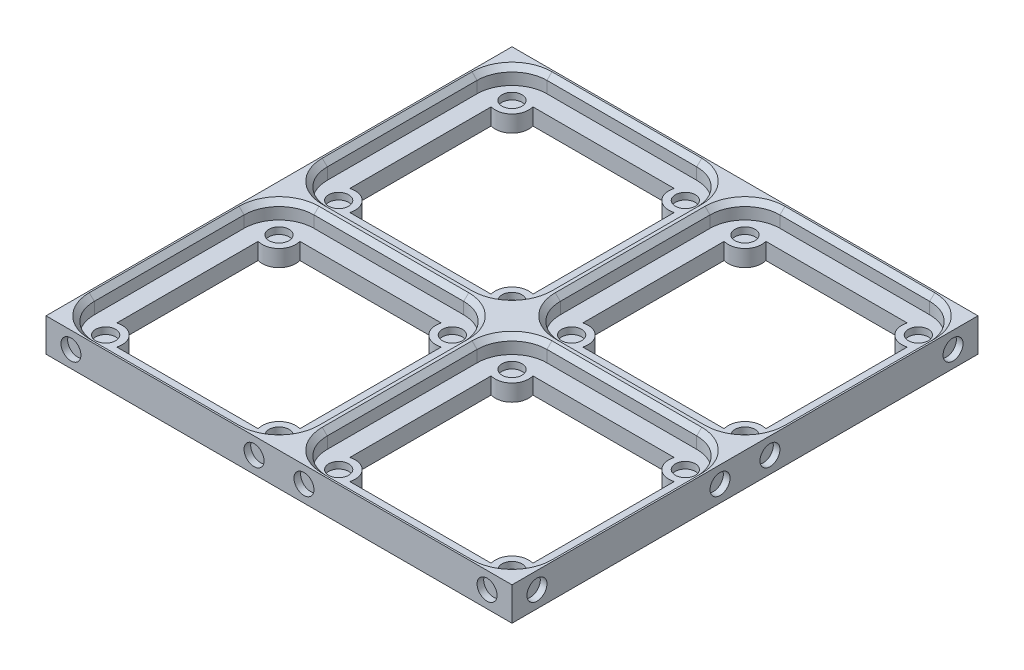
SolidWorks part; units mm, degrees
ref_plane "Front Plane" through (0, 0, 0) normal (0, 0, 1) x (1, 0, 0)
ref_plane "Top Plane" through (0, 0, 0) normal (0, 1, 0) x (1, 0, 0)
ref_plane "Right Plane" through (0, 0, 0) normal (1, 0, 0) x (0, 0, -1)
sketch "Sketch1" plane through (0, 0, 0) normal (0, 1, 0) x (1, 0, 0)
  line L1 (0, 0) -> (70, 0)
  line L2 (0, 0) -> (0, 70)
  line L3 (0, 70) -> (70, 70)
  line L4 (70, 0) -> (70, 70)
  dimension "D1" = 70
  dimension "D2" = 70
extrude "Boss-Extrude2" add sketch "Sketch1" along normal blind 7
sketch "Sketch3" plane through (0, 7, 0) normal (0, 1, 0) x (1, 0, 0)
  line L8 (2.5, 67.5) -> (2.5, 2.5)
  line L9 (2.5, 2.5) -> (67.5, 2.5)
  line L10 (67.5, 2.5) -> (67.5, 67.5)
  line L11 (67.5, 67.5) -> (2.5, 67.5)
  line L12 (2.5, 57.5) -> (2.5, 12.5)
  line L13 (12.5, 2.5) -> (57.5, 2.5)
  line L14 (67.5, 12.5) -> (67.5, 57.5)
  line L15 (57.5, 67.5) -> (12.5, 67.5)
  arc A0 (2.5, 12.5) -> (12.5, 2.5) centre (12.5, 12.5) ccw
  arc A1 (57.5, 2.5) -> (67.5, 12.5) centre (57.5, 12.5) ccw
  arc A2 (67.5, 57.5) -> (57.5, 67.5) centre (57.5, 57.5) ccw
  arc A3 (2.5, 57.5) -> (12.5, 67.5) centre (12.5, 57.5) cw
  dimension "D2" = 10
  dimension "D1" = 2.5
extrude "Cut-Extrude1" cut sketch "Sketch3" against normal blind 5
sketch "Sketch9" plane through (0, 0, 0) normal (0, -1, 0) x (1, 0, 0)
  line L1 (0, -70) -> (70, -70)
  line L2 (0, -70) -> (0, 0)
  line L3 (0, 0) -> (70, 0)
  line L4 (70, -70) -> (70, 0)
extrude "Boss-Extrude3" add sketch "Sketch9" along normal blind 5
sketch "Sketch20" plane through (0, 2, 0) normal (0, 1, 0) x (1, 0, 0)
  line L0 (35, 35) -> (8.9645, 61.0355) construction
  line L19 (12.5, 7.5) -> (57.5, 7.5)
  line L20 (62.5, 12.5) -> (62.5, 57.5)
  line L21 (57.5, 62.5) -> (12.5, 62.5)
  line L22 (7.5, 57.5) -> (7.5, 12.5)
  line L23 (13.7452, 7.5) -> (56.2548, 7.5)
  line L24 (62.5, 13.7452) -> (62.5, 56.2548)
  line L25 (56.2548, 62.5) -> (13.7452, 62.5)
  line L26 (7.5, 56.2548) -> (7.5, 13.7452)
  arc A0 (56.2548, 62.5) -> (62.5, 56.2548) centre (61.0355, 61.0355) ccw
  arc A1 (62.5, 13.7452) -> (56.2548, 7.5) centre (61.0355, 8.9645) ccw
  arc A2 (13.7452, 7.5) -> (7.5, 13.7452) centre (8.9645, 8.9645) ccw
  circle A4 centre (8.9645, 61.0355) radius 3
  circle A5 centre (8.9645, 8.9645) radius 3
  circle A6 centre (61.0355, 8.9645) radius 3
  circle A7 centre (61.0355, 61.0355) radius 3
  arc A21 (7.5, 56.2548) -> (13.7452, 62.5) centre (8.9645, 61.0355) ccw
  arc A24 (7.5, 12.5) -> (12.5, 7.5) centre (12.5, 12.5) ccw
  arc A25 (57.5, 7.5) -> (62.5, 12.5) centre (57.5, 12.5) ccw
  arc A26 (62.5, 57.5) -> (57.5, 62.5) centre (57.5, 57.5) ccw
  arc A27 (12.5, 62.5) -> (7.5, 57.5) centre (12.5, 57.5) ccw
  point P8 (35, 35)
  dimension "D2" = 6
  dimension "D3" = 4
  dimension "D4" = 36.8198
  dimension "D1" = 5
extrude "Cut-Extrude11" cut sketch "Sketch20" against normal through all contours L23 A1 L24 A0 L25 A21 L26 A2
sketch "Sketch21" plane through (0, 2, 0) normal (0, 1, 0) x (1, 0, 0)
  circle A0 centre (8.9645, 61.0355) radius 3
  circle A1 centre (61.0355, 61.0355) radius 3
  circle A2 centre (61.0355, 8.9645) radius 3
  circle A3 centre (8.9645, 8.9645) radius 3
extrude "Cut-Extrude12" cut sketch "Sketch21" against normal blind 2 contours A0 | A1 | A2 | A3
sketch "Sketch22" plane through (0, -5, 0) normal (0, -1, 0) x (1, 0, 0)
  line L0 (7.5, -13.7452) -> (7.5, -56.2548)
  line L1 (0, 0) -> (70, 0)
  line L2 (0, 0) -> (0, -70)
  line L3 (0, -70) -> (70, -70)
  line L4 (70, 0) -> (70, -70)
  line L6 (13.7452, -62.5) -> (56.2548, -62.5)
  line L8 (62.5, -56.2548) -> (62.5, -13.7452)
  line L10 (56.2548, -7.5) -> (13.7452, -7.5)
  arc A0 (7.5, -13.7452) -> (13.7452, -7.5) centre (8.9645, -8.9645) ccw
  arc A1 (56.2548, -7.5) -> (62.5, -13.7452) centre (61.0355, -8.9645) ccw
  arc A2 (62.5, -56.2548) -> (56.2548, -62.5) centre (61.0355, -61.0355) ccw
  arc A3 (13.7452, -62.5) -> (7.5, -56.2548) centre (8.9645, -61.0355) ccw
extrude "Cut-Extrude13" cut sketch "Sketch22" against normal blind 2
ref_plane "Plane2" through (0, 0, -35) normal (0, 0, 1) x (1, 0, 0)
ref_plane "Plane3" through (35, 0, 0) normal (-1, 0, 0) x (0, 0, 1)
sketch "Sketch27" plane through (0, 0, 0) normal (-1, 0, 0) x (0, 0, 1)
  line L0 (-70, -3) -> (-70, 7)
  line L1 (-70, 7) -> (-70, 2)
  line L2 (-70, 2) -> (-62.5, 2)
  line L3 (-35, -5.5) -> (-35, 5.5) construction
  circle A0 centre (-62.5, 2) radius 3
  circle A1 centre (-7.5, 2) radius 3
extrude "Cut-Extrude27" cut sketch "Sketch27" against normal blind 2
sketch "Sketch28" plane through (0, 0, 0) normal (0, 0, 1) x (1, 0, 0)
  line L0 (0, -3) -> (0, 7)
  line L1 (0, 7) -> (0, 2)
  line L2 (0, 2) -> (7.5, 2)
  line L3 (35, 5.5) -> (35, -5.5) construction
  circle A0 centre (7.5, 2) radius 3
  circle A1 centre (62.5, 2) radius 3
extrude "Cut-Extrude28" cut sketch "Sketch28" against normal blind 2
mirror "Mirror2" about plane through (0, 7, -70) normal (0, 0, 1) of bodies 126
mirror "Mirror3" about plane through (70, 7, 0) normal (-1, 0, 0) of bodies 130
sketch "Sketch30" plane through (0, 7, 0) normal (0, 1, 0) x (1, 0, 0)
  line L20 (2, 57.5) -> (2, 12.5)
  line L21 (12.5, 2) -> (57.5, 2)
  line L22 (68, 12.5) -> (68, 57.5)
  line L23 (57.5, 68) -> (12.5, 68)
  line L24 (2, 57.5) -> (2, 12.5)
  line L25 (12.5, 2) -> (57.5, 2)
  line L26 (68, 12.5) -> (68, 57.5)
  line L27 (57.5, 68) -> (12.5, 68)
  arc A24 (2, 12.5) -> (12.5, 2) centre (12.5, 12.5) ccw
  arc A25 (57.5, 2) -> (68, 12.5) centre (57.5, 12.5) ccw
  arc A26 (68, 57.5) -> (57.5, 68) centre (57.5, 57.5) ccw
  arc A27 (12.5, 68) -> (2, 57.5) centre (12.5, 57.5) ccw
  arc A28 (2, 12.5) -> (12.5, 2) centre (12.5, 12.5) ccw
  arc A29 (57.5, 2) -> (68, 12.5) centre (57.5, 12.5) ccw
  arc A30 (68, 57.5) -> (57.5, 68) centre (57.5, 57.5) ccw
  arc A31 (12.5, 68) -> (2, 57.5) centre (12.5, 57.5) ccw
  dimension "D1" = 0.5
extrude "Cut-Extrude29" cut sketch "Sketch30" against normal blind 5
sketch "Sketch31" plane through (0, 7, 0) normal (0, 1, 0) x (1, 0, 0)
  line L546 (68, 82.5) -> (68, 127.5)
  line L547 (12.5, 72) -> (57.5, 72)
  line L548 (2, 127.5) -> (2, 82.5)
  line L549 (57.5, 138) -> (12.5, 138)
  line L550 (68, 82.5) -> (68, 127.5)
  line L551 (12.5, 72) -> (57.5, 72)
  line L552 (2, 127.5) -> (2, 82.5)
  line L553 (57.5, 138) -> (12.5, 138)
  line L574 (82.5, 72) -> (127.5, 72)
  line L575 (138, 82.5) -> (138, 127.5)
  line L576 (72, 127.5) -> (72, 82.5)
  line L577 (127.5, 138) -> (82.5, 138)
  line L578 (82.5, 72) -> (127.5, 72)
  line L579 (138, 82.5) -> (138, 127.5)
  line L580 (72, 127.5) -> (72, 82.5)
  line L581 (127.5, 138) -> (82.5, 138)
  line L599 (72, 57.5) -> (72, 12.5)
  line L600 (82.5, 2) -> (127.5, 2)
  line L601 (138, 12.5) -> (138, 57.5)
  line L602 (127.5, 68) -> (82.5, 68)
  line L603 (72, 57.5) -> (72, 12.5)
  line L604 (82.5, 2) -> (127.5, 2)
  line L605 (138, 12.5) -> (138, 57.5)
  line L606 (127.5, 68) -> (82.5, 68)
  arc A564 (68, 127.5) -> (57.5, 138) centre (57.5, 127.5) ccw
  arc A565 (57.5, 72) -> (68, 82.5) centre (57.5, 82.5) ccw
  arc A566 (2, 82.5) -> (12.5, 72) centre (12.5, 82.5) ccw
  arc A567 (12.5, 138) -> (2, 127.5) centre (12.5, 127.5) ccw
  arc A568 (68, 127.5) -> (57.5, 138) centre (57.5, 127.5) ccw
  arc A569 (57.5, 72) -> (68, 82.5) centre (57.5, 82.5) ccw
  arc A570 (2, 82.5) -> (12.5, 72) centre (12.5, 82.5) ccw
  arc A571 (12.5, 138) -> (2, 127.5) centre (12.5, 127.5) ccw
  arc A588 (72, 82.5) -> (82.5, 72) centre (82.5, 82.5) ccw
  arc A589 (127.5, 72) -> (138, 82.5) centre (127.5, 82.5) ccw
  arc A590 (138, 127.5) -> (127.5, 138) centre (127.5, 127.5) ccw
  arc A591 (82.5, 138) -> (72, 127.5) centre (82.5, 127.5) ccw
  arc A592 (72, 82.5) -> (82.5, 72) centre (82.5, 82.5) ccw
  arc A593 (127.5, 72) -> (138, 82.5) centre (127.5, 82.5) ccw
  arc A594 (138, 127.5) -> (127.5, 138) centre (127.5, 127.5) ccw
  arc A595 (82.5, 138) -> (72, 127.5) centre (82.5, 127.5) ccw
  arc A615 (72, 12.5) -> (82.5, 2) centre (82.5, 12.5) ccw
  arc A616 (127.5, 2) -> (138, 12.5) centre (127.5, 12.5) ccw
  arc A617 (138, 57.5) -> (127.5, 68) centre (127.5, 57.5) ccw
  arc A618 (82.5, 68) -> (72, 57.5) centre (82.5, 57.5) ccw
  arc A619 (72, 12.5) -> (82.5, 2) centre (82.5, 12.5) ccw
  arc A620 (127.5, 2) -> (138, 12.5) centre (127.5, 12.5) ccw
  arc A621 (138, 57.5) -> (127.5, 68) centre (127.5, 57.5) ccw
  arc A622 (82.5, 68) -> (72, 57.5) centre (82.5, 57.5) ccw
  dimension "D1" = 0.5
  dimension "D2" = 0.5
  dimension "D3" = 0.5
extrude "Cut-Extrude30" cut sketch "Sketch31" against normal blind 5
chamfer "Chamfer1" distance 1.5 angle 45 32 edges at (134.9246, 7, -134.9246) (105, 7, -138) (138, 7, -105) (75.0754, 7, -134.9246) (134.9246, 7, -75.0754) (72, 7, -105) (105, 7, -72) (75.0754, 7, -75.0754) (5.0754, 7, -134.9246) (2, 7, -105) (35, 7, -138) (5.0754, 7, -75.0754) (64.9246, 7, -134.9246) (35, 7, -72) (68, 7, -105) (64.9246, 7, -75.0754) (5.0754, 7, -64.9246) (2, 7, -35) (35, 7, -68) (5.0754, 7, -5.0754) (64.9246, 7, -64.9246) (35, 7, -2) (68, 7, -35) (64.9246, 7, -5.0754) (105, 7, -68) (75.0754, 7, -64.9246) (134.9246, 7, -64.9246) (72, 7, -35) (138, 7, -35) (75.0754, 7, -5.0754) (134.9246, 7, -5.0754) (105, 7, -2)
